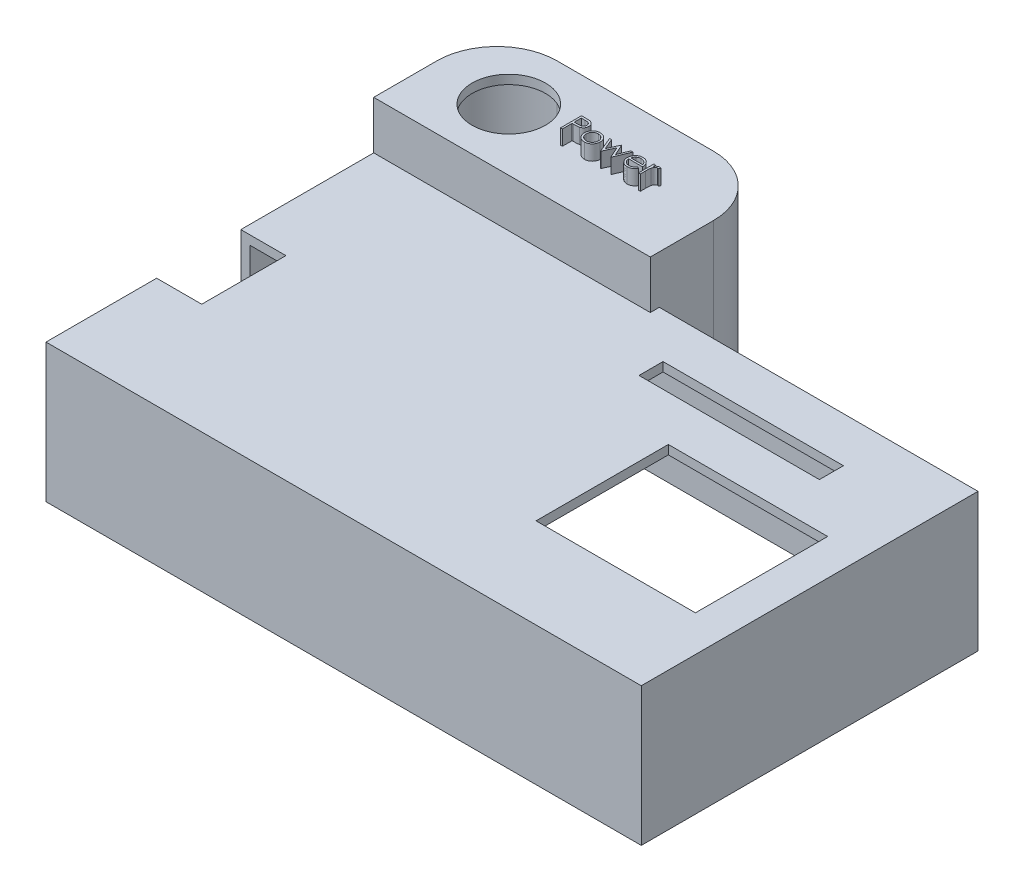
SolidWorks part; units mm, degrees
ref_plane "Front Plane" through (0, 0, 0) normal (0, 0, 1) x (1, 0, 0)
ref_plane "Top Plane" through (0, 0, 0) normal (0, 1, 0) x (1, 0, 0)
ref_plane "Right Plane" through (0, 0, 0) normal (1, 0, 0) x (0, 0, -1)
sketch "Sketch1" plane through (0, 0, 0) normal (0, 1, 0) x (1, 0, 0)
  line L1 (49.5, -28) -> (-49.5, -28)
  line L2 (49.5, -28) -> (49.5, 28)
  line L3 (49.5, 28) -> (-49.5, 28)
  line L4 (-49.5, -28) -> (-49.5, 28)
  line L5 (49.5, -28) -> (-49.5, 28) construction
  line L6 (49.5, 28) -> (-49.5, -28) construction
  point P0 (0, 0)
  dimension "D1" = 56
  dimension "D2" = 99
extrude "Boss-Extrude1" add sketch "Sketch1" along normal blind 23
sketch "Sketch3" plane through (0, 0, 0) normal (0, -1, 0) x (1, 0, 0)
  line L1 (-48, 26.5) -> (48, 26.5)
  line L2 (-48, 26.5) -> (-48, -26.5)
  line L3 (-48, -26.5) -> (48, -26.5)
  line L4 (48, 26.5) -> (48, -26.5)
  line L5 (-48, 26.5) -> (48, -26.5) construction
  line L6 (-48, -26.5) -> (48, 26.5) construction
  point P0 (0, 0)
  dimension "D1" = 96
  dimension "D2" = 53
extrude "Cut-Extrude1" cut sketch "Sketch3" against normal blind 21.5
sketch "Sketch4" plane through (0, 23, 0) normal (0, 1, 0) x (1, 0, 0)
  line L0 (-49.5, 28) -> (-49.5, -28) construction
  line L1 (-49.5, 4.4) -> (-42, 4.4)
  line L2 (-49.5, 4.4) -> (-49.5, -9.6)
  line L3 (-49.5, -9.6) -> (-42, -9.6)
  line L4 (-42, 4.4) -> (-42, -9.6)
  line L5 (49.5, 28) -> (-49.5, 28) construction
  circle A0 centre (-40.1664, 19.5284) radius 6
  dimension "D1" = 12
  dimension "D2" = 14
  dimension "D3" = 7.5
  dimension "D4" = 23.6
extrude "Cut-Extrude4" cut sketch "Sketch4" against normal blind 11 contours L2 L1 L4 L3
sketch "Sketch9" plane through (0, 0, 0) normal (0, -1, 0) x (1, 0, 0)
  line L0 (-48, -26.5) -> (48, -26.5) construction
  line L5 (-3.5, -26.5) -> (-49.5, -26.5)
  line L6 (-3.5, -26.5) -> (-3.5, -37)
  line L7 (-13.5, -47) -> (-39.5, -47)
  line L8 (-49.5, -26.5) -> (-49.5, -37)
  line L9 (-49.5, -28) -> (-49.5, 28) construction
  arc A0 (-39.5, -47) -> (-49.5, -37) centre (-39.5, -37) cw
  arc A1 (-3.5, -37) -> (-13.5, -47) centre (-13.5, -37) cw
  point P10 (-49.5, -47)
  point P13 (-3.5, -47)
  dimension "D4" = 10
  dimension "D1" = 20.5
  dimension "D2" = 46
  dimension "D3" = 0
extrude "Boss-Extrude5" add sketch "Sketch9" against normal blind 31
sketch "Sketch14" plane through (0, 0, 0) normal (0, -1, 0) x (-1, 0, 0)
  line L0 (3.5, 37) -> (3.5, 28) construction
  line L1 (5, 28) -> (48, 28)
  line L2 (5, 28) -> (5, 35.5)
  line L3 (15, 45.5) -> (38, 45.5)
  line L4 (48, 28) -> (48, 35.5)
  line L5 (49.5, 37) -> (49.5, -28) construction
  line L6 (39.5, 47) -> (13.5, 47) construction
  line L7 (48, 26.5) -> (-48, 26.5) construction
  arc A0 (5, 35.5) -> (15, 45.5) centre (15, 35.5) cw
  arc A1 (38, 45.5) -> (48, 35.5) centre (38, 35.5) cw
  dimension "D5" = 10
  dimension "D1" = 1.5
  dimension "D2" = 1.5
  dimension "D3" = 1.5
  dimension "D4" = 1.5
extrude "Cut-Extrude8" cut sketch "Sketch14" against normal blind 29.5
sketch "Sketch16" plane through (0, 0, -26.5) normal (0, 0, 1) x (1, 0, 0)
  line L0 (-48, 21.5) -> (48, 21.5) construction
  line L1 (-45.9875, 20) -> (-8.2349, 20)
  line L2 (-45.9875, 20) -> (-45.9875, 4)
  line L3 (-45.9875, 4) -> (-8.2349, 4)
  line L4 (-8.2349, 20) -> (-8.2349, 4)
  line L5 (-48, 0) -> (48, 0) construction
  dimension "D1" = 1.5
  dimension "D2" = 4
extrude "Cut-Extrude10" cut sketch "Sketch16" against normal blind 2
sketch "Sketch17" plane through (0, 29.5, 0) normal (0, -1, 0) x (-1, 0, 0)
  line L1 (38, 45.5) -> (15, 45.5) construction
  circle A0 centre (37.2816, 36.75) radius 6.1
  dimension "D1" = 12.2
  dimension "D2" = 8.75
extrude "Cut-Extrude11" cut sketch "Sketch17" against normal blind 2
sketch "Sketch18" plane through (0, 31, 0) normal (0, 1, 0) x (1, 0, 0)
  text T0 "Power"
extrude "Boss-Extrude6" add sketch "Sketch18" along normal blind 2.5
sketch "Sketch19" plane through (0, 23, 0) normal (0, 1, 0) x (1, 0, 0)
  line L2 (-49.5, -28) -> (49.5, -28) construction
  line L5 (-48, 4.4) -> (-48, -9.6) construction
  line L6 (-48, 26.5) -> (43.5, 26.5) construction
  line L7 (-48, 26.5) -> (-48, -26.5) construction
  line L8 (-48, -26.5) -> (43.5, -26.5) construction
  line L9 (43.5, 26.5) -> (43.5, -26.5) construction
  line L10 (49.5, 28) -> (-3.5, 28) construction
  line L13 (43.5, 9) -> (17, 9)
  line L14 (43.5, 9) -> (43.5, -13)
  line L15 (43.5, -13) -> (17, -13)
  line L16 (17, 9) -> (17, -13)
  dimension "D1" = 1.5
  dimension "D2" = 91.5
  dimension "D3" = 53
  dimension "D4" = 0
  dimension "D5" = 17.5
  dimension "D6" = 1.5
  dimension "D7" = 22
  dimension "D8" = 26.5
extrude "Cut-Extrude12" cut sketch "Sketch19" against normal blind 2
sketch "Sketch20" plane through (0, 23, 0) normal (0, 1, 0) x (1, 0, 0)
  line L0 (49.5, 28) -> (-3.5, 28) construction
  line L1 (4.6186, 20.5) -> (34.6186, 20.5)
  line L2 (4.6186, 20.5) -> (4.6186, 16.5)
  line L3 (4.6186, 16.5) -> (34.6186, 16.5)
  line L4 (34.6186, 20.5) -> (34.6186, 16.5)
  dimension "D1" = 4
  dimension "D2" = 7.5
  dimension "D3" = 30
extrude "Cut-Extrude13" cut sketch "Sketch20" against normal blind 2
